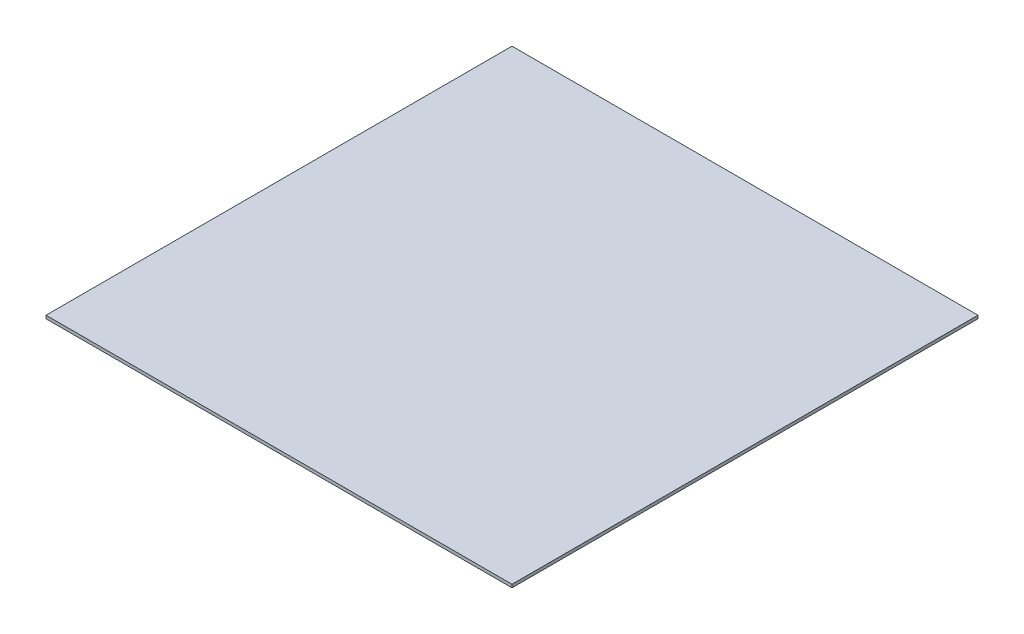
SolidWorks part; units mm, degrees
ref_plane "Front" through (0, 0, 0) normal (0, 0, 1) x (1, 0, 0)
ref_plane "Top" through (0, 0, 0) normal (0, 1, 0) x (1, 0, 0)
ref_plane "Right" through (0, 0, 0) normal (1, 0, 0) x (0, 0, -1)
sketch "Sketch1" plane through (0, 0, 0) normal (0, 1, 0) x (1, 0, 0)
  line L1 (-7.5, -7.5) -> (7.5, -7.5)
  line L2 (-7.5, -7.5) -> (-7.5, 7.5)
  line L3 (-7.5, 7.5) -> (7.5, 7.5)
  line L4 (7.5, -7.5) -> (7.5, 7.5)
  line L5 (-7.5, -7.5) -> (7.5, 7.5) construction
  line L6 (-7.5, 7.5) -> (7.5, -7.5) construction
  point P0 (0, 0)
  dimension "D1" = 15
extrude "Boss-Extrude1" add sketch "Sketch1" along normal blind 0.1
